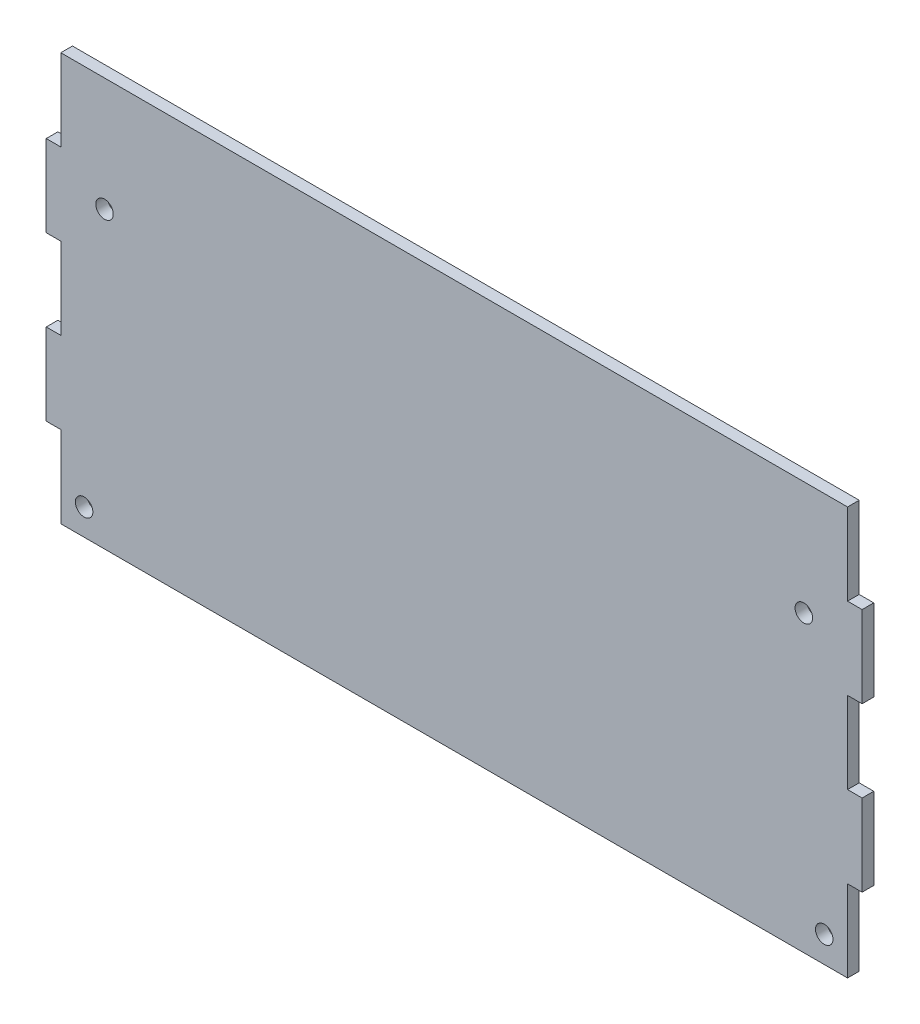
SolidWorks part; units mm, degrees
ref_plane "Front Plane" through (0, 0, 0) normal (0, 0, 1) x (1, 0, 0)
ref_plane "Top Plane" through (0, 0, 0) normal (0, 1, 0) x (1, 0, 0)
ref_plane "Right Plane" through (0, 0, 0) normal (1, 0, 0) x (0, 0, -1)
sketch "Sketch1" plane through (0, 0, 0) normal (0, 0, 1) x (1, 0, 0)
  line L1 (135, 55) -> (-135, 55)
  line L2 (135, 55) -> (135, -55)
  line L3 (135, -55) -> (-135, -55)
  line L4 (-135, 55) -> (-135, -55)
  line L5 (135, 55) -> (-135, -55) construction
  line L6 (135, -55) -> (-135, 55) construction
  point P0 (0, 0)
  dimension "D1" = 270
  dimension "D2" = 110
extrude "Boss-Extrude1" add sketch "Sketch1" along normal blind 4
sketch "Sketch9" plane through (0, 0, 0) normal (0, 0, -1) x (-1, 0, 0)
  circle A0 centre (-120, 46) radius 3 construction
  circle A1 centre (-127, -46) radius 3 construction
  circle A2 centre (120, 46) radius 3 construction
  circle A3 centre (127, -46) radius 3 construction
  circle A10 centre (-120, 46) radius 3
  circle A11 centre (-127, -46) radius 3
  circle A12 centre (120, 46) radius 3
  circle A13 centre (127, -46) radius 3
extrude "Cut-Extrude1" cut sketch "Sketch9" against normal through all
sketch "Sketch10" plane through (0, 55, 0) normal (0, 1, 0) x (1, 0, 0)
  line L4 (135, 0) -> (-135, 0)
  line L5 (-135, 0) -> (-135, -4)
  line L6 (-135, -4) -> (135, -4)
  line L7 (135, -4) -> (135, 0)
  line L8 (135, 0) -> (-135, 0)
  line L9 (-135, 0) -> (-135, -4)
  line L10 (-135, -4) -> (135, -4)
  line L11 (135, -4) -> (135, 0)
  dimension "D1" = 0
extrude "Boss-Extrude2" add sketch "Sketch10" along normal blind 30
sketch "Esquisse1" plane through (135, 0, 0) normal (1, 0, 0) x (0, 0, -1)
  line L0 (0, -55) -> (0, 85) construction
  line L1 (0, -27) -> (-4, -27)
  line L2 (0, -27) -> (0, 1)
  line L3 (0, 1) -> (-4, 1)
  line L4 (-4, -27) -> (-4, 1)
  line L5 (-4, -55) -> (-4, 85) construction
  line L7 (0, 29) -> (-4, 29)
  line L8 (0, 29) -> (0, 57)
  line L9 (0, 57) -> (-4, 57)
  line L10 (-4, 29) -> (-4, 57)
  dimension "D1" = 28
  dimension "D2" = 28
  dimension "D3" = 28
  dimension "D4" = 28
extrude "Boss.-Extru.1" add sketch "Esquisse1" along normal blind 5
ref_plane "Plan1" through (0, 0, 0) normal (1, 0, 0) x (0, 0, -1)
mirror "Symétrie1" about plane through (0, 0, 0) normal (1, 0, 0) of "Boss.-Extru.1"
